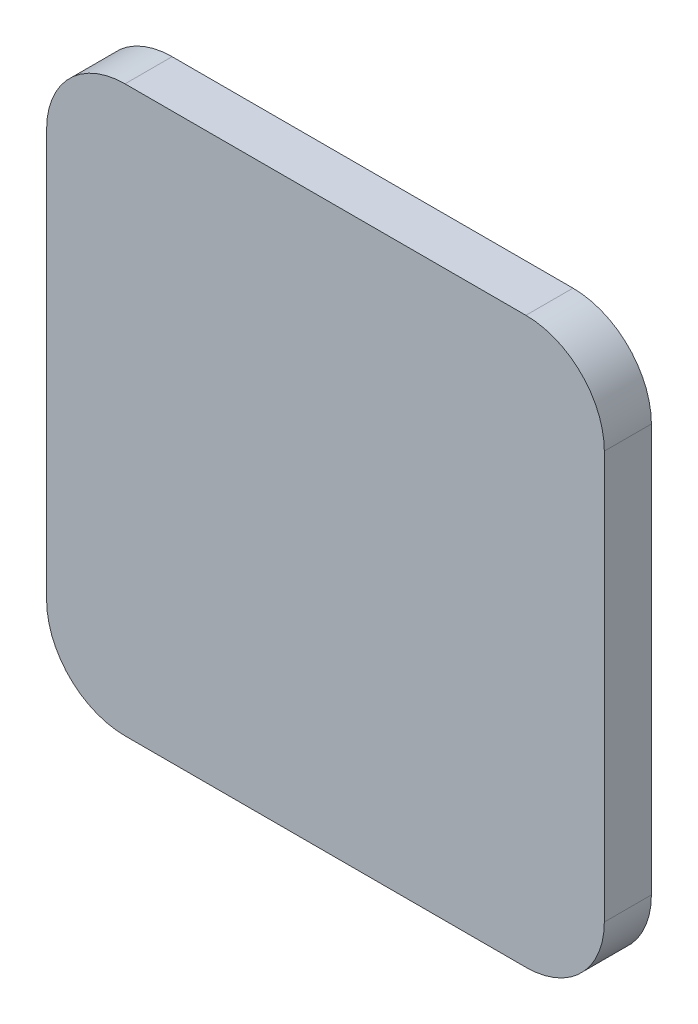
SolidWorks part; units mm, degrees
ref_plane "Front Plane" through (0, 0, 0) normal (0, 0, 1) x (1, 0, 0)
ref_plane "Top Plane" through (0, 0, 0) normal (0, 1, 0) x (1, 0, 0)
ref_plane "Right Plane" through (0, 0, 0) normal (1, 0, 0) x (0, 0, -1)
ref_plane "Plane1" through (0, 0, 6) normal (0, 0, 1) x (1, 0, 0)
sketch "Sketch2" plane through (0, 0, 6) normal (0, 0, 1) x (1, 0, 0)
  line L1 (-12.5571, 18) -> (13, 18)
  line L2 (-17.5571, 13) -> (-17.5571, -13)
  line L3 (-12.5571, -18) -> (13, -18)
  line L4 (18, 13) -> (18, -13)
  line L5 (18, 17) -> (18, -17) construction
  line L6 (-17, 18) -> (17, 18) construction
  line L7 (17, -18) -> (-17, -18) construction
  line L10 (-17.5571, -16.5274) -> (-17.5571, 15.4726) construction
  arc A0 (18, -13) -> (13, -18) centre (13, -13) cw
  arc A1 (-12.5571, -18) -> (-17.5571, -13) centre (-12.5571, -13) cw
  arc A2 (-17.5571, 13) -> (-12.5571, 18) centre (-12.5571, 13) cw
  arc A3 (13, 18) -> (18, 13) centre (13, 13) cw
  dimension "D1" = 5
extrude "Boss-Extrude1" add sketch "Sketch2" along normal blind 3
